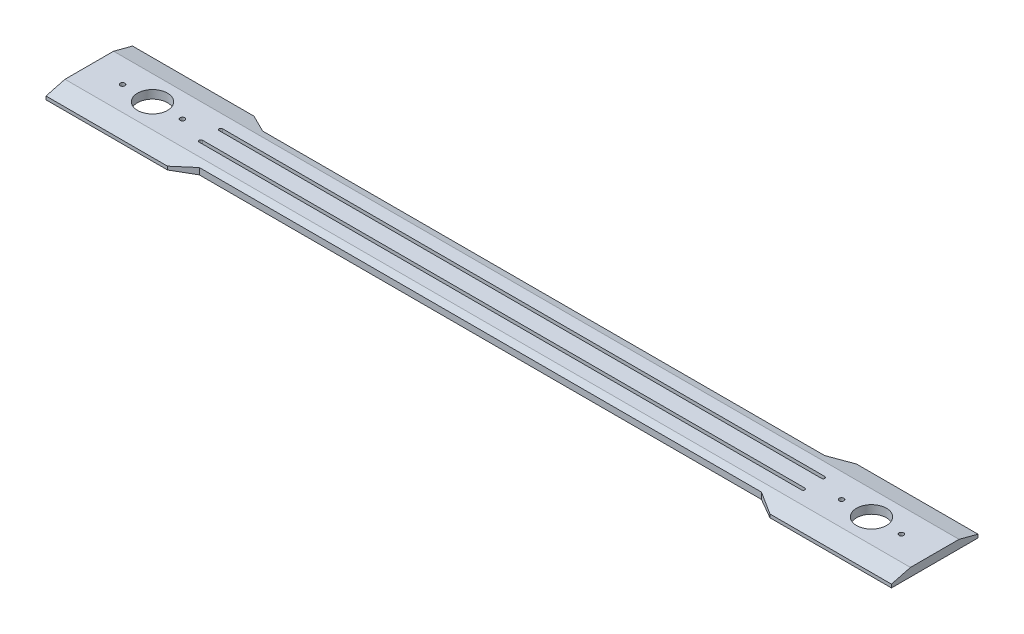
SolidWorks part; units mm, degrees
ref_plane "前视基准面" through (0, 0, 0) normal (0, 0, 1) x (1, 0, 0)
ref_plane "上视基准面" through (0, 0, 0) normal (0, 1, 0) x (1, 0, 0)
ref_plane "右视基准面" through (0, 0, 0) normal (1, 0, 0) x (0, 0, -1)
sketch "草图1" plane through (0, 0, 0) normal (0, 1, 0) x (1, 0, 0)
  line L0 (-1270, 130) -> (-1270, -130)
  line L1 (-1270, -130) -> (-905, -130)
  line L2 (-905, -130) -> (-844.3782, -95)
  line L3 (-844.3782, -95) -> (844.3782, -95)
  line L4 (0, -95) -> (0, 0) construction
  line L5 (0, 0) -> (-1270, 0) construction
  line L6 (0, 0) -> (0, 92.3684) construction
  line L7 (0, 0) -> (75.8852, 0) construction
  line L8 (905, -130) -> (844.3782, -95)
  line L9 (1270, -130) -> (905, -130)
  line L10 (1270, 130) -> (1270, -130)
  line L11 (1270, 130) -> (905, 130)
  line L12 (905, 130) -> (844.3782, 95)
  line L13 (-844.3782, 95) -> (844.3782, 95)
  line L14 (-905, 130) -> (-844.3782, 95)
  line L15 (-1270, 130) -> (-905, 130)
  point P15 (1270, 0)
  dimension "D1" = 260
  dimension "D2" = 2540
  dimension "D3" = 365
  dimension "D4" = 35
  dimension "D5" = 150
extrude "凸台-拉伸1" add sketch "草图1" along normal blind 25
sketch "草图2" plane through (0, 25, 0) normal (0, 1, 0) x (1, 0, 0)
  line L0 (-1270, 130) -> (-1270, -130) construction
  circle A0 centre (-1080, 0) radius 45
  circle A1 centre (-1170, 0) radius 7
  circle A2 centre (-990, 0) radius 7
  point P9 (0, 0)
  point P10 (0, 0)
  dimension "D1" = 90
  dimension "D3" = 14
  dimension "D4" = 14
  dimension "D2" = 190
  dimension "D5" = 90
  dimension "D6" = 90
extrude "切除-拉伸1" cut sketch "草图2" against normal through all
mirror "镜向1" about plane through (0, 0, 0) normal (1, 0, 0) of "切除-拉伸1"
sketch "草图3" plane through (0, 25, 0) normal (0, 1, 0) x (1, 0, 0)
  line L0 (-905, -30) -> (905, -30) construction
  line L1 (-1270, 130) -> (-1270, -130) construction
  line L2 (-844.3782, -95) -> (844.3782, -95) construction
  line L3 (-905, -35) -> (905, -35)
  line L4 (-905, -25) -> (905, -25)
  arc A0 (-905, -35) -> (-905, -25) centre (-905, -30) cw
  arc A1 (905, -35) -> (905, -25) centre (905, -30) ccw
  point P4 (915.5774, -52.0412)
  point P5 (0, 0)
  dimension "D1" = 365
  dimension "D2" = 65
  dimension "D3" = 5
  dimension "D4" = 5
extrude "切除-拉伸2" cut sketch "草图3" against normal through all
mirror "镜向2" about plane through (0, 0, 0) normal (0, 0, 1) of "切除-拉伸2"
sketch "草图6" plane through (1270, 0, 0) normal (1, 0, 0) x (0, 0, -1)
  line L0 (-73, 25) -> (-130, 10)
  line L1 (-130, 25) -> (130, 25) construction
  line L2 (-130, 25) -> (-130, 0) construction
  line L3 (-73, 25) -> (-130, 25)
  line L4 (-130, 25) -> (-130, 10)
  line L5 (0, 13.75) -> (0, -13.75) construction
  line L6 (73, 25) -> (130, 10)
  line L7 (73, 25) -> (130, 25)
  line L8 (130, 25) -> (130, 10)
  dimension "D1" = 57
  dimension "D2" = 10
extrude "切除-拉伸3" cut sketch "草图6" against normal through all
